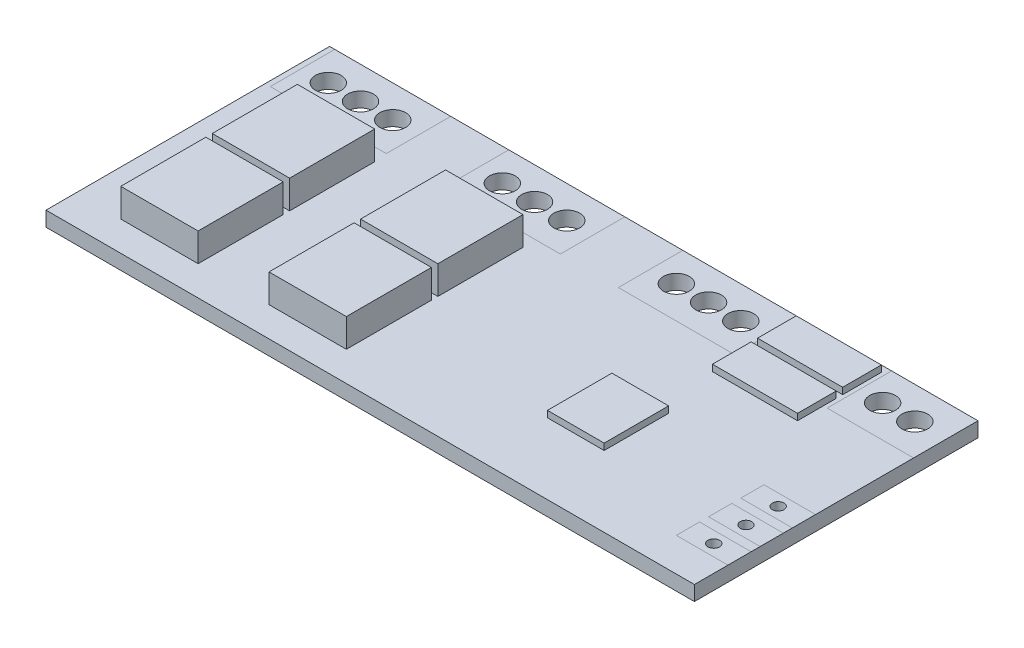
SolidWorks part; units mm, degrees
ref_plane "Alzado" through (0, 0, 0) normal (0, 0, 1) x (1, 0, 0)
ref_plane "Planta" through (0, 0, 0) normal (0, 1, 0) x (1, 0, 0)
ref_plane "Vista lateral" through (0, 0, 0) normal (1, 0, 0) x (0, 0, -1)
sketch "Croquis1" plane through (0, 0, 0) normal (0, 1, 0) x (1, 0, 0)
  line L0 (0, -11) -> (0, 11) construction
  line L1 (-25.15, 11) -> (25.15, 11)
  line L2 (-25.15, 11) -> (-25.15, -11)
  line L3 (-25.15, -11) -> (25.15, -11)
  line L4 (25.15, 11) -> (25.15, -11)
  line L5 (-25.15, 11) -> (25.15, -11) construction
  line L6 (-25.15, -11) -> (25.15, 11) construction
  line L7 (-13.5, 11) -> (-13.5, -11) construction
  circle A0 centre (23.15, -7.5) radius 0.45
  circle A3 centre (23.15, -5) radius 0.45
  circle A4 centre (23.15, -2.5) radius 0.45
  circle A5 centre (4.25, 8.5) radius 1
  circle A6 centre (6.75, 8.5) radius 1
  circle A7 centre (9.25, 8.5) radius 1
  circle A8 centre (-9.25, 8.5) radius 1
  circle A9 centre (-6.75, 8.5) radius 1
  circle A10 centre (-4.25, 8.5) radius 1
  circle A11 centre (-22.75, 8.5) radius 1
  circle A12 centre (-20.25, 8.5) radius 1
  circle A13 centre (-17.75, 8.5) radius 1
  circle A14 centre (22.75, 8.5) radius 1
  circle A15 centre (20.25, 8.5) radius 1
  point P0 (0, 0)
  point P9 (0, 0)
  dimension "D3" = 0.9
  dimension "D9" = 2
  dimension "D1" = 50.3
  dimension "D2" = 22
  dimension "D4" = 3.5
  dimension "D5" = 2
  dimension "D7" = 2.5
  dimension "D10" = 2.5
  dimension "D11" = 2.5
  dimension "D12" = 8.5
  dimension "D13" = 4.25
  dimension "D6" = 3
  dimension "D8" = 3
extrude "Saliente-Extruir1" add sketch "Croquis1" along normal blind 1.15
sketch "Croquis2" plane through (0, 1.15, 0) normal (0, 1, 0) x (1, 0, 0)
  line L0 (-25.15, -1.85) -> (25.15, -1.85) construction
  line L1 (-21.65, 5) -> (-15.65, 5)
  line L2 (-21.65, 5) -> (-21.65, -1.6)
  line L3 (-21.65, -1.6) -> (-15.65, -1.6)
  line L4 (-15.65, 5) -> (-15.65, -1.6)
  line L5 (-25.15, 11) -> (-25.15, -11) construction
  line L6 (25.15, -11) -> (25.15, 11) construction
  line L7 (-12.9, 11) -> (-12.9, -11) construction
  line L8 (25.15, 11) -> (-25.15, 11) construction
  line L9 (-25.15, -11) -> (25.15, -11) construction
  line L10 (-4.15, -1.6) -> (-10.15, -1.6)
  line L11 (-10.15, 5) -> (-10.15, -1.6)
  line L12 (-4.15, 5) -> (-10.15, 5)
  line L13 (-4.15, 5) -> (-4.15, -1.6)
  line L14 (-4.15, -8.7) -> (-4.15, -2.1)
  line L15 (-4.15, -8.7) -> (-10.15, -8.7)
  line L16 (-10.15, -8.7) -> (-10.15, -2.1)
  line L17 (-4.15, -2.1) -> (-10.15, -2.1)
  line L18 (-21.65, -2.1) -> (-15.65, -2.1)
  line L19 (-15.65, -8.7) -> (-15.65, -2.1)
  line L20 (-21.65, -8.7) -> (-15.65, -8.7)
  line L21 (-21.65, -8.7) -> (-21.65, -2.1)
  point P16 (-25.15, -2.9204)
  dimension "D1" = 6
  dimension "D2" = 6.6
  dimension "D3" = 3.5
  dimension "D4" = 6
  dimension "D5" = 2.75
  dimension "D6" = 0.25
extrude "Saliente-Extruir2" add sketch "Croquis2" along normal blind 2.2 separate body
sketch "Croquis3" plane through (0, 1.15, 0) normal (0, 1, 0) x (1, 0, 0)
  line L0 (25.15, -11) -> (25.15, 11) construction
  line L1 (8.25, -0.5) -> (12.65, -0.5)
  line L2 (8.25, -0.5) -> (8.25, -5.5)
  line L3 (8.25, -5.5) -> (12.65, -5.5)
  line L4 (12.65, -0.5) -> (12.65, -5.5)
  line L5 (11.55, 10.5) -> (18.15, 10.5)
  line L6 (11.55, 10.5) -> (11.55, 7.5)
  line L7 (11.55, 7.5) -> (18.15, 7.5)
  line L8 (18.15, 10.5) -> (18.15, 7.5)
  line L9 (11.55, 7) -> (18.15, 7)
  line L10 (11.55, 7) -> (11.55, 4)
  line L11 (11.55, 4) -> (18.15, 4)
  line L12 (18.15, 7) -> (18.15, 4)
  line L13 (-25.15, -11) -> (25.15, -11) construction
  line L14 (25.15, 11) -> (-25.15, 11) construction
  dimension "D1" = 4.4
  dimension "D2" = 5
  dimension "D3" = 12.5
  dimension "D4" = 5.5
  dimension "D5" = 6.6
  dimension "D6" = 0.5
  dimension "D7" = 0.5
  dimension "D8" = 3
  dimension "D9" = 7
extrude "Saliente-Extruir3" add sketch "Croquis3" along normal blind 0.5 separate body
sketch "Croquis4" plane through (0, 1.15, 0) normal (0, 1, 0) x (1, 0, 0)
  line L0 (25.15, 11) -> (-25.15, 11) construction
  line L1 (11.25, 6) -> (2.25, 6)
  line L2 (11.25, 6) -> (11.25, 11)
  line L3 (11.25, 11) -> (2.25, 11)
  line L4 (2.25, 6) -> (2.25, 11)
  line L5 (11.25, 6) -> (2.25, 11) construction
  line L6 (11.25, 11) -> (2.25, 6) construction
  line L7 (-4.25, 8.5) -> (4.25, 8.5) construction
  line L8 (0, 8.5) -> (0, 11) construction
  line L9 (-11.25, 11) -> (-2.25, 11)
  line L10 (-2.25, 6) -> (-2.25, 11)
  line L11 (-11.25, 6) -> (-2.25, 6)
  line L12 (-11.25, 6) -> (-11.25, 11)
  line L13 (-17.75, 8.5) -> (-9.25, 8.5) construction
  line L14 (-13.5, 8.5) -> (-13.5, 11) construction
  line L15 (-15.75, 6) -> (-15.75, 11)
  line L16 (-15.75, 6) -> (-24.75, 6)
  line L17 (-24.75, 6) -> (-24.75, 11)
  line L18 (-15.75, 11) -> (-24.75, 11)
  line L19 (25.15, -11) -> (25.15, 11) construction
  line L20 (18.45, 11) -> (25.15, 11)
  line L21 (18.45, 11) -> (18.45, 6)
  line L22 (18.45, 6) -> (25.15, 6)
  line L23 (25.15, 11) -> (25.15, 6)
  line L25 (18.15, 7.5) -> (18.15, 10.5) construction
  line L26 (23.15, -5) -> (25.15, -5) construction
  line L27 (21.15, -8.4) -> (25.15, -8.4)
  line L28 (21.15, -8.4) -> (21.15, -6.6)
  line L29 (21.15, -6.6) -> (25.15, -6.6)
  line L30 (25.15, -8.4) -> (25.15, -6.6)
  line L31 (21.15, -8.4) -> (25.15, -6.6) construction
  line L32 (21.15, -6.6) -> (25.15, -8.4) construction
  line L33 (21.15, -3.4) -> (25.15, -3.4)
  line L34 (25.15, -1.6) -> (25.15, -3.4)
  line L35 (21.15, -1.6) -> (25.15, -1.6)
  line L36 (21.15, -1.6) -> (21.15, -3.4)
  line L38 (21.15, -4.1) -> (25.15, -4.1)
  line L39 (21.15, -4.1) -> (21.15, -5.9)
  line L40 (21.15, -5.9) -> (25.15, -5.9)
  line L41 (25.15, -4.1) -> (25.15, -5.9)
  line L42 (21.15, -4.1) -> (25.15, -5.9) construction
  line L43 (21.15, -5.9) -> (25.15, -4.1) construction
  point P0 (6.75, 8.5)
  point P34 (23.15, -7.5)
  dimension "D1" = 9
  dimension "D2" = 0.3
  dimension "D3" = 1.8
split line "Línea de partición1"
